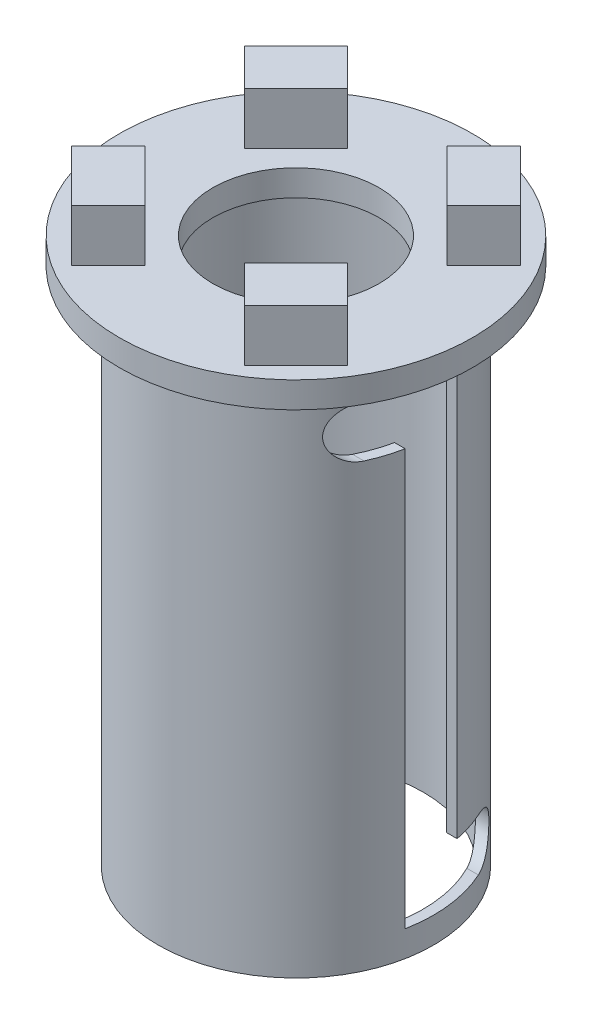
SolidWorks part; units mm, degrees
ref_plane "Front Plane" through (0, 0, 0) normal (0, 0, 1) x (1, 0, 0)
ref_plane "Top Plane" through (0, 0, 0) normal (0, 1, 0) x (1, 0, 0)
ref_plane "Right Plane" through (0, 0, 0) normal (1, 0, 0) x (0, 0, -1)
sketch "Sketch2" plane through (0, 0, 0) normal (0, 1, 0) x (1, 0, 0)
  circle A0 centre (0, 0) radius 13.25
  circle A1 centre (0, 0) radius 12.25
  dimension "D1" = 26.5
  dimension "D2" = 24.5
extrude "Boss-Extrude1" add sketch "Sketch2" along normal blind 50
ref_plane "Plane4" through (13.25, 0, 0) normal (1, 0, 0) x (0, 0, -1)
sketch "Sketch4" plane through (13.25, 0, 0) normal (1, 0, 0) x (0, 0, -1)
  line L1 (-2.5, 47.5) -> (2.5, 47.5)
  line L2 (-2.5, 47.5) -> (-2.5, 2.5)
  line L3 (-2.5, 2.5) -> (2.5, 2.5)
  line L4 (2.5, 47.5) -> (2.5, 2.5)
  line L5 (12.25, 50) -> (-12.25, 50) construction
  line L6 (-13.25, 0) -> (13.25, 0) construction
  line L7 (-2.5, 47.5) -> (-5.5, 47.5)
  line L8 (-2.5, 47.5) -> (-2.5, 42.5)
  line L9 (-2.5, 42.5) -> (-5.5, 42.5)
  line L10 (-5.5, 47.5) -> (-5.5, 42.5)
  line L11 (2.5, 2.5) -> (5.5, 2.5)
  line L12 (2.5, 2.5) -> (2.5, 7.5)
  line L13 (2.5, 7.5) -> (5.5, 7.5)
  line L14 (5.5, 2.5) -> (5.5, 7.5)
  circle A0 centre (5.5, 5) radius 2.5
  circle A1 centre (-5.5, 45) radius 2.5
  point P8 (0, 47.5)
  point P10 (0, 2.5)
  dimension "D1" = 2.5
  dimension "D2" = 2.5
  dimension "D3" = 5
  dimension "D4" = 5
  dimension "D5" = 3
  dimension "D6" = 5
  dimension "D7" = 3
extrude "Cut-Extrude2" cut sketch "Sketch4" against normal blind 5 contours L10 A1 | L10 A1 | L4 L1 L2 L3 | L14 A0 | A0 L13 L4 L11 | L14 A0 | A1 L9 L2 L7
sketch "Sketch6" plane through (0, 50, 0) normal (0, 1, 0) x (1, 0, 0)
  circle A0 centre (0, 0) radius 8
  circle A1 centre (0, 0) radius 17
  dimension "D1" = 16
  dimension "D2" = 34
extrude "Boss-Extrude3" add sketch "Sketch6" along normal blind 2.5
sketch "Sketch7" plane through (0, 52.5, 0) normal (0, 1, 0) x (1, 0, 0)
  line L1 (-9.3692, -9.3692) -> (9.3692, -9.3692)
  line L2 (-9.3692, -9.3692) -> (-9.3692, 9.3692)
  line L3 (-9.3692, 9.3692) -> (9.3692, 9.3692)
  line L4 (9.3692, -9.3692) -> (9.3692, 9.3692)
  line L5 (-9.3692, -9.3692) -> (9.3692, 9.3692) construction
  line L6 (-9.3692, 9.3692) -> (9.3692, -9.3692) construction
  line L10 (4.7937, 9.7435) -> (9.7435, 4.7937)
  line L11 (4.7937, 9.7435) -> (8.3293, 13.279)
  line L12 (9.7435, 4.7937) -> (13.279, 8.3293)
  line L13 (8.3293, 13.279) -> (13.279, 8.3293)
  line L14 (-4.7937, 9.7435) -> (-9.7435, 4.7937)
  line L15 (-4.7937, 9.7435) -> (-8.3293, 13.279)
  line L16 (-9.7435, 4.7937) -> (-13.279, 8.3293)
  line L17 (-8.3293, 13.279) -> (-13.279, 8.3293)
  line L18 (-4.7937, -9.7435) -> (-8.3293, -13.279)
  line L19 (-4.7937, -9.7435) -> (-9.7435, -4.7937)
  line L20 (-8.3293, -13.279) -> (-13.279, -8.3293)
  line L21 (-9.7435, -4.7937) -> (-13.279, -8.3293)
  line L22 (4.7937, -9.7435) -> (8.3293, -13.279)
  line L23 (4.7937, -9.7435) -> (9.7435, -4.7937)
  line L24 (8.3293, -13.279) -> (13.279, -8.3293)
  line L25 (9.7435, -4.7937) -> (13.279, -8.3293)
  circle A0 centre (0, 0) radius 13.25 construction
  circle A1 centre (0, 0) radius 13.25
  point P7 (6.5615, 11.5113)
  point P10 (11.5113, 6.5615)
  point P13 (7.2686, 7.2686)
  point P14 (-11.5113, 6.5615)
  point P17 (-6.5615, 11.5113)
  point P20 (-7.2686, 7.2686)
  point P21 (-6.5615, -11.5113)
  point P24 (-11.5113, -6.5615)
  point P27 (-7.2686, -7.2686)
  point P28 (6.5615, -11.5113)
  point P31 (11.5113, -6.5615)
  point P34 (7.2686, -7.2686)
  dimension "D1" = 7
  dimension "D2" = 5
  dimension "D3" = 7
  dimension "D4" = 5
  dimension "D5" = 7
  dimension "D6" = 5
  dimension "D7" = 7
  dimension "D8" = 5
extrude "Boss-Extrude4" add sketch "Sketch7" along normal blind 5 contours A1 L22 L24 L25 | A1 L21 L20 L18 | A1 L15 L17 L16 | L15 A1 L3 L14 | L2 A1 L16 L14 | L14 L3 L2 | L1 A1 L18 L19 | L1 L19 L2 | L21 A1 L2 L19 | L4 A1 L25 L23 | L23 L1 L4 | L22 A1 L1 L23 | A1 L12 L13 L11 | L3 A1 L11 L10 | L3 L10 L4 | L12 A1 L4 L10
scale "Scale1" scale about centroid uniform scaling yes scale factor 0.8
